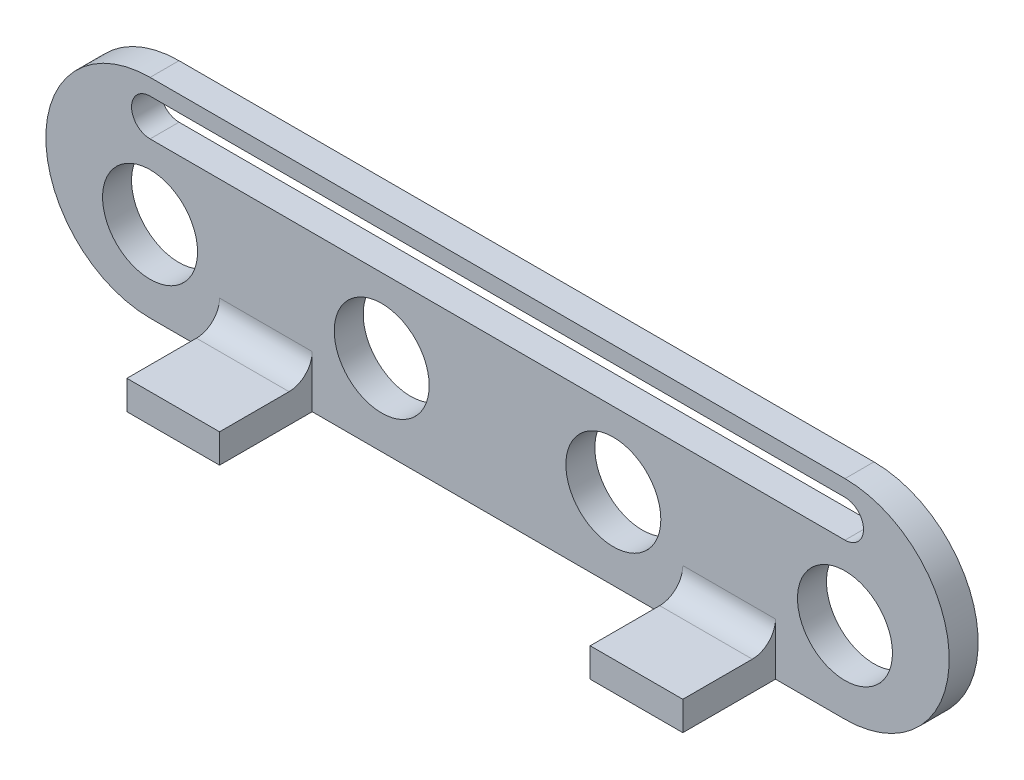
SolidWorks part; units mm, degrees
ref_plane "Front Plane" through (0, 0, 0) normal (0, 0, 1) x (1, 0, 0)
ref_plane "Top Plane" through (0, 0, 0) normal (0, 1, 0) x (1, 0, 0)
ref_plane "Right Plane" through (0, 0, 0) normal (1, 0, 0) x (0, 0, -1)
sketch "Sketch1" plane through (0, 0, 0) normal (0, 0, 1) x (1, 0, 0)
  line L0 (-38.1, 0) -> (38.1, 0) construction
  line L1 (-38.1, 11.43) -> (38.1, 11.43)
  line L2 (-38.1, -11.43) -> (38.1, -11.43)
  line L3 (12.7, 0) -> (-12.7, 0) construction
  arc A0 (-38.1, 11.43) -> (-38.1, -11.43) centre (-38.1, 0) ccw
  arc A1 (38.1, -11.43) -> (38.1, 11.43) centre (38.1, 0) ccw
  circle A6 centre (-38.1, -2.54) radius 5.207
  circle A7 centre (-12.7, -2.54) radius 5.207
  circle A8 centre (12.7, -2.54) radius 5.207
  circle A9 centre (38.1, -2.54) radius 5.207
  point P2 (0, 0)
  dimension "D2" = 11.43
  dimension "D3" = 10.414
  dimension "D6" = 25.4
  dimension "D1" = 76.2
  dimension "D5" = 2.54
  dimension "D4" = 4
extrude "Boss-Extrude1" add sketch "Sketch1" along normal blind 3.175
sketch "Sketch2" plane through (0, 0, 3.175) normal (0, 0, 1) x (1, 0, 0)
  line L0 (-38.1, -11.43) -> (38.1, -11.43) construction
  line L5 (-12.7, -2.54) -> (-38.1, -2.54) construction
  line L6 (-25.4, -2.54) -> (-25.4, -8.255) construction
  line L7 (0, -1.7463) -> (0, 1.7463) construction
  line L8 (-30.48, -11.43) -> (-20.32, -11.43)
  line L9 (-20.32, -8.255) -> (-20.32, -11.43)
  line L10 (-30.48, -8.255) -> (-20.32, -8.255)
  line L11 (-30.48, -8.255) -> (-30.48, -11.43)
  line L12 (30.48, -8.255) -> (20.32, -8.255)
  line L13 (30.48, -8.255) -> (30.48, -11.43)
  line L14 (30.48, -11.43) -> (20.32, -11.43)
  line L15 (20.32, -8.255) -> (20.32, -11.43)
  dimension "D1" = 10.16
  dimension "D2" = 3.175
extrude "Boss-Extrude2" add sketch "Sketch2" along normal blind 10.16
fillet "Fillet1" radius 2.54 2 edges at (25.4, -8.255, 3.175) (-25.4, -8.255, 3.175)
sketch "Sketch4" plane through (0, 0, 3.175) normal (0, 0, 1) x (1, 0, 0)
  line L0 (-38.1, 7.62) -> (38.1, 7.62) construction
  line L1 (-38.1, 9.652) -> (38.1, 9.652)
  line L2 (-38.1, 5.588) -> (38.1, 5.588)
  line L3 (38.1, 11.43) -> (-38.1, 11.43) construction
  arc A0 (-38.1, 9.652) -> (-38.1, 5.588) centre (-38.1, 7.62) ccw
  arc A1 (38.1, 5.588) -> (38.1, 9.652) centre (38.1, 7.62) ccw
  point P2 (0, 7.62)
  dimension "D1" = 4.064
  dimension "D2" = 76.2
  dimension "D3" = 3.81
extrude "Cut-Extrude2" cut sketch "Sketch4" against normal up to next
